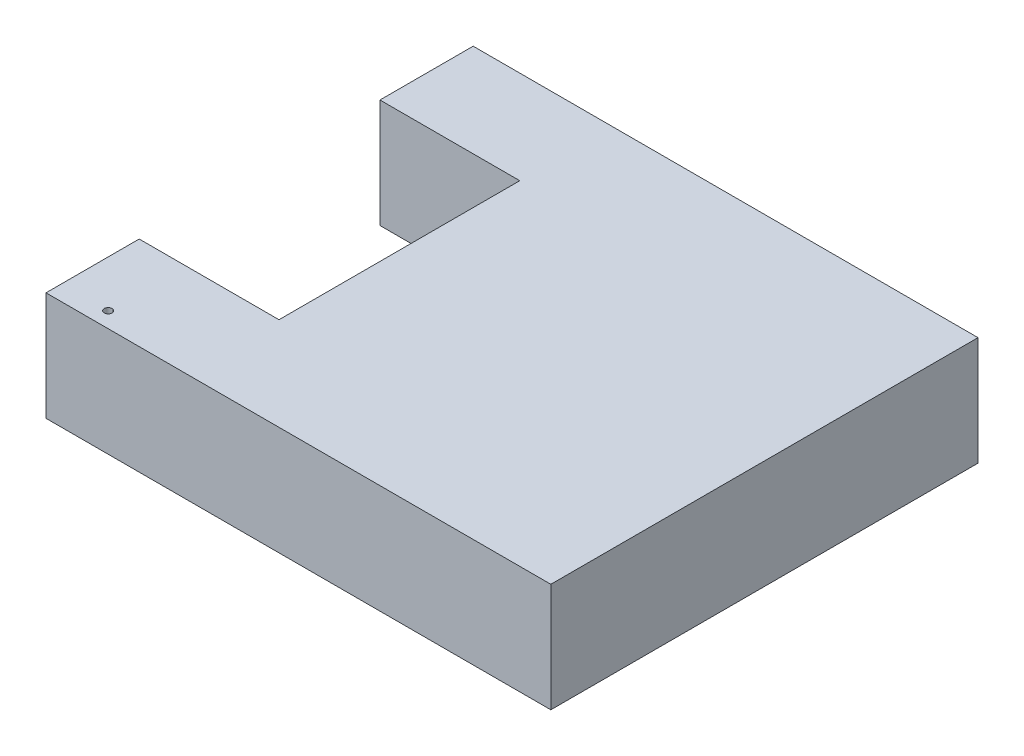
SolidWorks part; units mm, degrees
ref_plane "Front Plane" through (0, 0, 0) normal (0, 0, 1) x (1, 0, 0)
ref_plane "Top Plane" through (0, 0, 0) normal (0, 1, 0) x (1, 0, 0)
ref_plane "Right Plane" through (0, 0, 0) normal (1, 0, 0) x (0, 0, -1)
sketch "Sketch2" plane through (0, 0, 0) normal (0, 1, 0) x (1, 0, 0)
  line L0 (0, 546.1) -> (0, 698.5)
  line L1 (0, 0) -> (825.5, 0)
  line L2 (0, 0) -> (0, 152.4)
  line L3 (0, 698.5) -> (825.5, 698.5)
  line L4 (825.5, 0) -> (825.5, 698.5)
  line L5 (0, 152.4) -> (228.6, 152.4)
  line L7 (0, 546.1) -> (228.6, 546.1)
  line L8 (228.6, 152.4) -> (228.6, 546.1)
  dimension "D1" = 825.5
  dimension "D2" = 698.5
  dimension "D3" = 152.4
  dimension "D4" = 152.4
  dimension "D5" = 228.6
extrude "Boss-Extrude1" add sketch "Sketch2" along normal blind 177.8
sketch "Sketch3" plane through (0, 0, 0) normal (0, -1, 0) x (-1, 0, 0)
  line L0 (0, 152.4) -> (0, 0) construction
  line L2 (-228.6, 152.4) -> (0, 152.4) construction
  circle A0 centre (-76.2, 25.4) radius 6.35
  point P6 (0, 0)
  point P7 (-12.7, 25.637)
  dimension "D1" = 76.2
  dimension "D2" = 127
  dimension "D3" = 12.7
extrude "Cut-Extrude1" cut sketch "Sketch3" against normal through all
